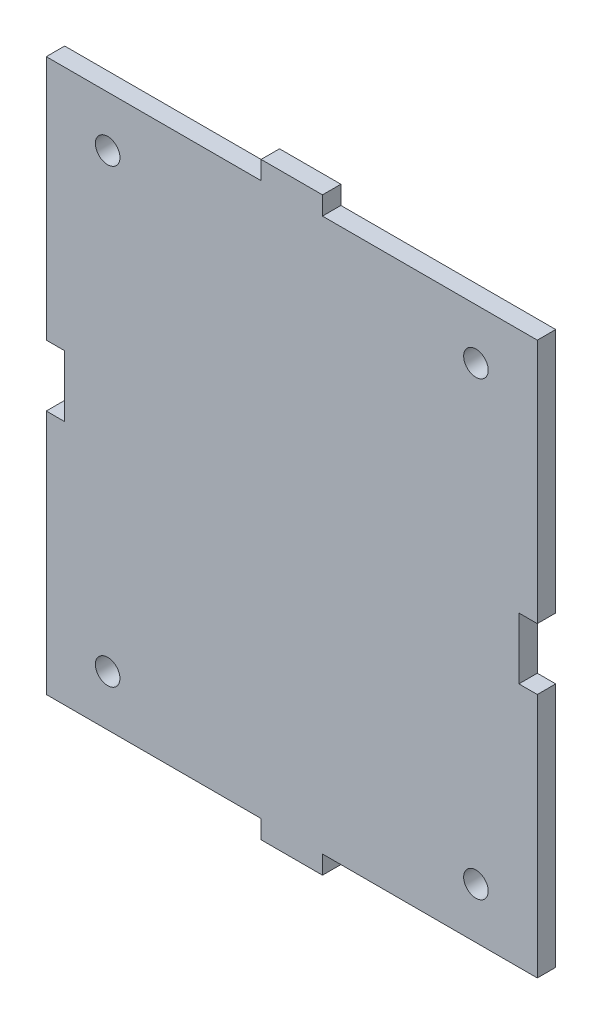
SolidWorks part; units mm, degrees
ref_plane "Front Plane" through (0, 0, 0) normal (0, 0, 1) x (1, 0, 0)
ref_plane "Top Plane" through (0, 0, 0) normal (0, 1, 0) x (1, 0, 0)
ref_plane "Right Plane" through (0, 0, 0) normal (1, 0, 0) x (0, 0, -1)
sketch "Sketch1" plane through (0, 0, 0) normal (0, 0, 1) x (1, 0, 0)
  line L0 (5, 8.25) -> (40, 8.25)
  line L5 (0, 0) -> (28.5, 0) construction
  line L6 (-5, 11.25) -> (5, 11.25)
  line L7 (28.5, 0) -> (30, 0) construction
  line L8 (0, 0) -> (0, -15.5615) construction
  line L9 (30, -2) -> (30, -71.5) construction
  line L10 (30, -36.75) -> (0, -36.75) construction
  line L11 (28.5, -73.5) -> (30, -73.5) construction
  line L12 (-5, 11.25) -> (-5, 8.25)
  line L13 (0, -73.5) -> (28.5, -73.5) construction
  line L14 (-28.5, -73.5) -> (-30, -73.5) construction
  line L15 (-30, -2) -> (-30, -71.5) construction
  line L16 (-28.5, 0) -> (-30, 0) construction
  line L18 (-40, -81.75) -> (-5, -81.75)
  line L19 (-40, -81.75) -> (-40, -41.75)
  line L20 (-40, 8.25) -> (-5, 8.25)
  line L21 (40, -81.75) -> (40, -41.75)
  line L22 (-40, -81.75) -> (40, 8.25) construction
  line L23 (-40, 8.25) -> (40, -81.75) construction
  line L24 (5, 11.25) -> (5, 8.25)
  line L25 (5, -84.75) -> (5, -81.75)
  line L26 (-5, -84.75) -> (-5, -81.75)
  line L27 (-5, -84.75) -> (5, -84.75)
  line L28 (5, -81.75) -> (40, -81.75)
  line L29 (40, -31.75) -> (40, 8.25)
  line L30 (37, -41.75) -> (40, -41.75)
  line L31 (37, -41.75) -> (37, -31.75)
  line L32 (37, -31.75) -> (40, -31.75)
  line L34 (-37, -31.75) -> (-40, -31.75)
  line L35 (-37, -41.75) -> (-37, -31.75)
  line L36 (-37, -41.75) -> (-40, -41.75)
  line L37 (-40, -31.75) -> (-40, 8.25)
  circle A0 centre (30, 0) radius 2
  circle A1 centre (30, -73.5) radius 2
  circle A2 centre (-30, -73.5) radius 2
  circle A3 centre (-30, 0) radius 2
  point P0 (0, 0)
  point P1 (0, 8.25)
  point P36 (0, -81.75)
  point P37 (40, -36.75)
  point P46 (-40, -36.75)
  dimension "D2" = 4
  dimension "D1" = 28.5
extrude "Boss-Extrude1" add sketch "Sketch1" along normal blind 3
